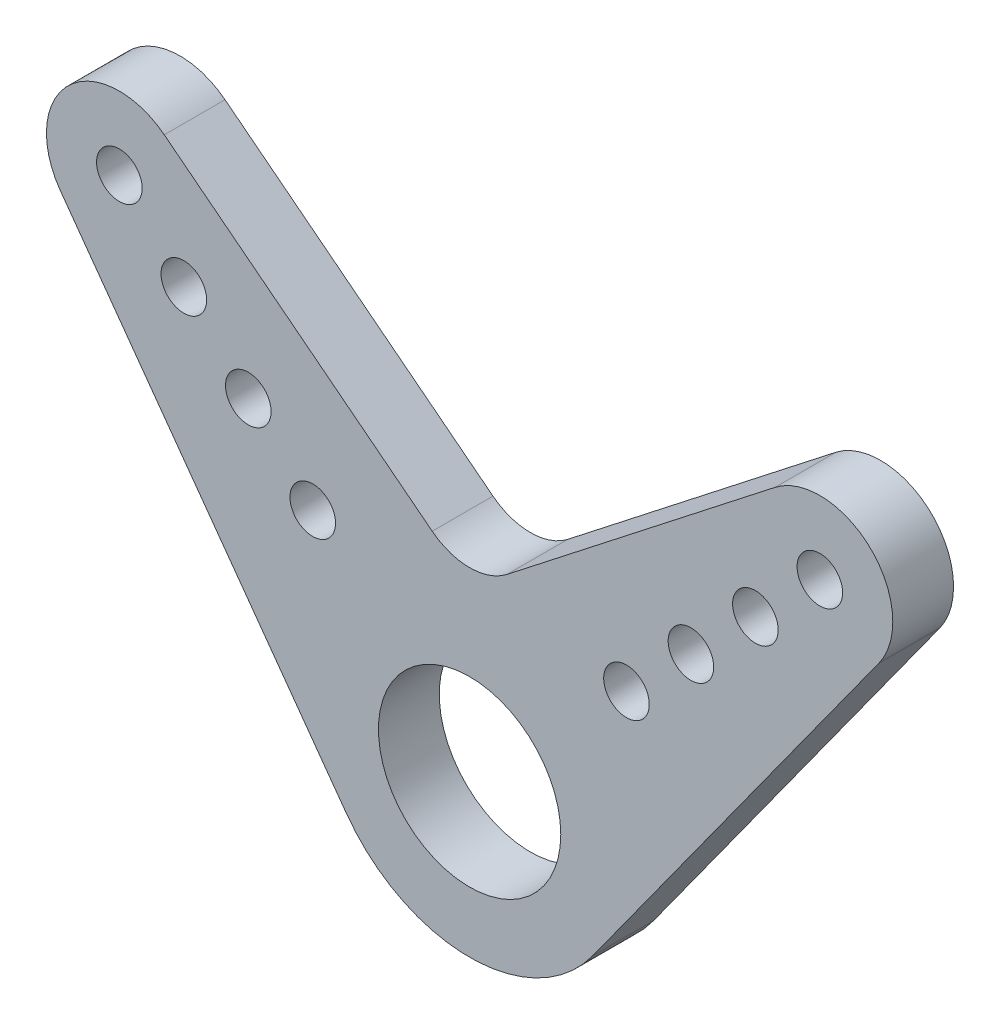
SolidWorks part; units mm, degrees
ref_plane "Front Plane" through (0, 0, 0) normal (0, 0, 1) x (1, 0, 0)
ref_plane "Top Plane" through (0, 0, 0) normal (0, 1, 0) x (1, 0, 0)
ref_plane "Right Plane" through (0, 0, 0) normal (1, 0, 0) x (0, 0, -1)
sketch "Sketch1" plane through (0, 0, 0) normal (0, 0, 1) x (1, 0, 0)
  line L0 (0, 25.4846) -> (0, 0) construction
  line L1 (0, 0) -> (11.5258, 11.5258) construction
  line L2 (0, 0) -> (0, -13.4288) construction
  line L3 (13.4719, 10.1212) -> (4.0542, -2.9263)
  line L4 (10.0483, 13.4171) -> (1.2313, 6.5285)
  line L5 (-10.0483, 13.4171) -> (-1.2313, 6.5285)
  line L6 (-13.4719, 10.1212) -> (-4.0542, -2.9263)
  circle A0 centre (0, 0) radius 3
  arc A1 (-4.0542, -2.9263) -> (4.0542, -2.9263) centre (0, 0) ccw
  arc A2 (13.4719, 10.1212) -> (10.0483, 13.4171) centre (11.5258, 11.5258) ccw
  arc A3 (1.2313, 6.5285) -> (-1.2313, 6.5285) centre (0, 8.1045) cw
  arc A4 (-13.4719, 10.1212) -> (-10.0483, 13.4171) centre (-11.5258, 11.5258) cw
  dimension "D1" = 6
  dimension "D3" = 5
  dimension "D4" = 2.4
  dimension "D6" = 2
  dimension "D2" = 45
  dimension "D5" = 16.3
  dimension "D7" = 9.178
  dimension "D8" = 7
extrude "Extrude1" add sketch "Sketch1" along normal blind 2
sketch "Sketch2" plane through (0, 0, 2) normal (0, 0, 1) x (1, 0, 0)
  line L0 (11.5258, 11.5258) -> (0, 0) construction
  line L1 (0, 0) -> (0, 14.1752) construction
  circle A0 centre (11.5258, 11.5258) radius 0.75
  circle A1 centre (9.4045, 9.4045) radius 0.75
  circle A2 centre (7.2832, 7.2832) radius 0.75
  circle A3 centre (5.1619, 5.1619) radius 0.75
  circle A4 centre (-5.1619, 5.1619) radius 0.75
  circle A5 centre (-7.2832, 7.2832) radius 0.75
  circle A6 centre (-9.4045, 9.4045) radius 0.75
  circle A7 centre (-11.5258, 11.5258) radius 0.75
  dimension "D1" = 1.5
  dimension "D2" = 3
  dimension "D3" = 3
  dimension "D4" = 3
extrude "Extrude2" cut sketch "Sketch2" against normal blind 2
sketch "Sketch3" plane through (0, 0, 2) normal (0, 0, 1) x (1, 0, 0)
  point P0 (11.5258, 11.5258)
  point P1 (-11.5258, 11.5258)
